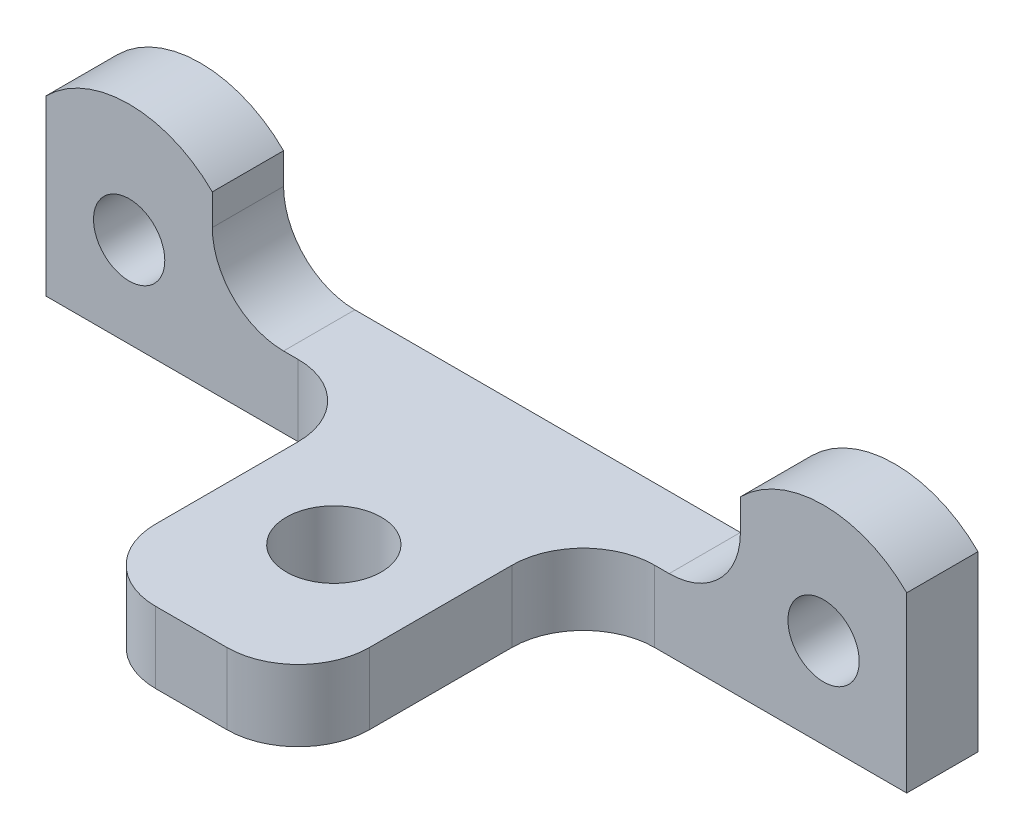
SolidWorks part; units mm, degrees
ref_plane "Plan de face" through (0, 0, 0) normal (0, 0, 1) x (1, 0, 0)
ref_plane "Plan de dessus" through (0, 0, 0) normal (0, 1, 0) x (1, 0, 0)
ref_plane "Plan de droite" through (0, 0, 0) normal (1, 0, 0) x (0, 0, -1)
sketch "Esquisse1" plane through (0, 0, 0) normal (0, 0, 1) x (1, 0, 0)
  line L0 (0, 0) -> (0, 3.8) construction
  line L1 (-14.615, 3.8) -> (14.615, 3.8) construction
  line L2 (-18.115, 7.3) -> (-18.115, 0)
  line L3 (-18.115, 0) -> (18.115, 0)
  line L4 (18.115, 0) -> (18.115, 7.3)
  line L5 (-11.115, 7.3) -> (-11.115, 3)
  line L6 (-11.115, 3) -> (11.115, 3)
  line L7 (11.115, 3) -> (11.115, 7.3)
  line L8 (-11.115, 3) -> (-18.115, 3) construction
  line L9 (11.115, 3) -> (18.115, 3) construction
  circle A0 centre (-14.615, 3.8) radius 1.5
  circle A1 centre (14.615, 3.8) radius 1.5
  arc A2 (-18.115, 7.3) -> (-11.115, 7.3) centre (-14.615, 3.8) cw
  arc A3 (11.115, 7.3) -> (18.115, 7.3) centre (14.615, 3.8) cw
  point P5 (0, 3.8)
  point P16 (-14.615, 3)
  point P19 (14.615, 3)
  dimension "D5" = 3
  dimension "D6" = 3
  dimension "D1" = 29.23
  dimension "D2" = 3.8
  dimension "D3" = 0
  dimension "D4" = 0
  dimension "D9" = 3
  dimension "D10" = 0
  dimension "D11" = 0
  dimension "D12" = 0
  dimension "D13" = 3.5
extrude "Boss.-Extru.1" add sketch "Esquisse1" along normal blind 3
sketch "Esquisse2" plane through (0, 0, 3) normal (0, 0, 1) x (1, 0, 0)
  line L0 (11.115, 3) -> (-11.115, 3) construction
  line L1 (-4.5, 3) -> (4.5, 3)
  line L2 (-4.5, 3) -> (-4.5, 0)
  line L3 (-4.5, 0) -> (4.5, 0)
  line L4 (4.5, 3) -> (4.5, 0)
  line L5 (-18.115, 0) -> (18.115, 0) construction
  point P8 (0, 3)
  dimension "D1" = 0
  dimension "D2" = 9
extrude "Boss.-Extru.2" add sketch "Esquisse2" along normal blind 12
sketch "Esquisse3" plane through (0, 3, 0) normal (0, 1, 0) x (1, 0, 0)
  circle A0 centre (0, -9) radius 2
  dimension "D1" = 4
  dimension "D2" = 0
  dimension "D3" = 6
extrude "Enlèv. mat.-Extru.1" cut sketch "Esquisse3" against normal through all
fillet "Congé1" radius 3 6 edges at (11.115, 3, 1.5) (-11.115, 3, 1.5) (4.5, 1.5, 3) (4.5, 1.5, 15) (-4.5, 1.5, 15) (-4.5, 1.5, 3)
